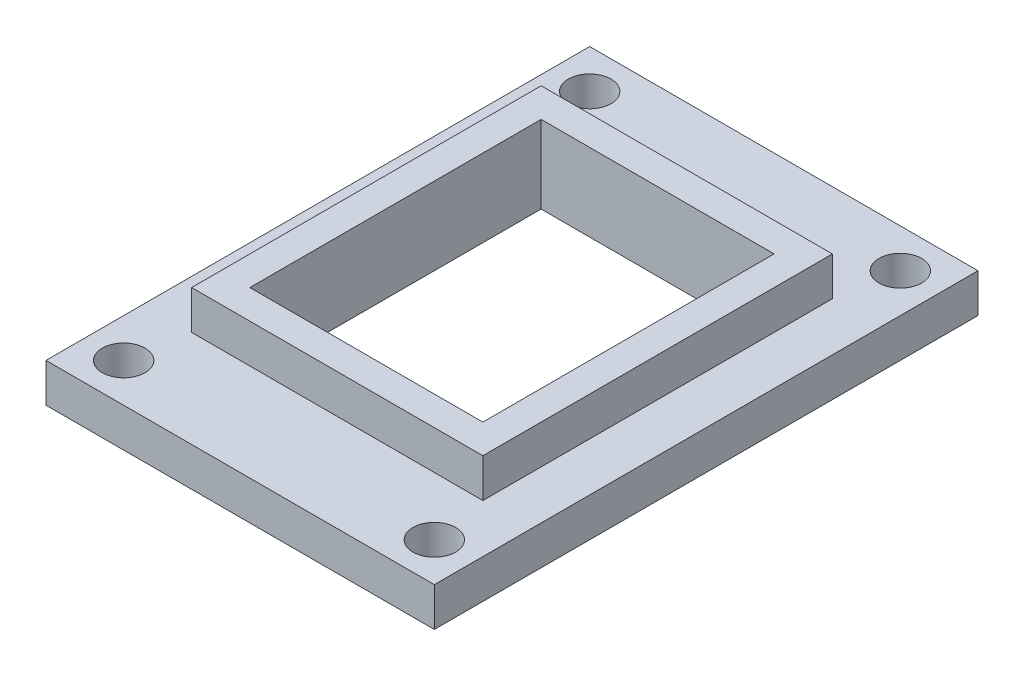
SolidWorks part; units mm, degrees
ref_plane "Front Plane" through (0, 0, 0) normal (0, 0, 1) x (1, 0, 0)
ref_plane "Top Plane" through (0, 0, 0) normal (0, 1, 0) x (1, 0, 0)
ref_plane "Right Plane" through (0, 0, 0) normal (1, 0, 0) x (0, 0, -1)
sketch "Sketch1" plane through (0, 0, 0) normal (0, 1, 0) x (1, 0, 0)
  line L0 (9.525, -11.43) -> (9.525, 11.43)
  line L1 (7.62, -9.525) -> (-7.62, -9.525)
  line L2 (7.62, -9.525) -> (7.62, 9.525)
  line L3 (7.62, 9.525) -> (-7.62, 9.525)
  line L4 (-7.62, -9.525) -> (-7.62, 9.525)
  line L5 (7.62, -9.525) -> (-7.62, 9.525) construction
  line L6 (7.62, 9.525) -> (-7.62, -9.525) construction
  line L7 (9.525, 11.43) -> (-9.525, 11.43)
  line L8 (-9.525, -11.43) -> (-9.525, 11.43)
  line L9 (9.525, -11.43) -> (-9.525, -11.43)
  point P0 (0, 0)
  dimension "D1" = 19.05
  dimension "D2" = 15.24
  dimension "D3" = 1.905
extrude "Boss-Extrude1" add sketch "Sketch1" along normal blind 5.08
sketch "Sketch3" plane through (0, 0, 0) normal (0, 1, 0) x (1, 0, 0)
  line L0 (-7.62, 0) -> (49992.38, 0) construction
  line L1 (-7.62, 9.525) -> (-7.62, -9.525) construction
  line L3 (0, 19.685) -> (0, -49980.315) construction
  line L4 (-9.525, -11.43) -> (9.525, -11.43)
  line L5 (9.525, -11.43) -> (9.525, 11.43)
  line L6 (9.525, 11.43) -> (-9.525, 11.43)
  line L7 (-9.525, 11.43) -> (-9.525, -11.43)
  line L8 (-9.525, -11.43) -> (9.525, -11.43)
  line L9 (9.525, -11.43) -> (9.525, 11.43)
  line L10 (9.525, 11.43) -> (-9.525, 11.43)
  line L11 (-9.525, 11.43) -> (-9.525, -11.43)
  line L12 (-7.62, -9.525) -> (7.62, -9.525) construction
  line L13 (-12.7, 17.78) -> (12.7, 17.78)
  line L14 (-12.7, 17.78) -> (-12.7, -17.78)
  line L15 (-12.7, -17.78) -> (12.7, -17.78)
  line L16 (12.7, 17.78) -> (12.7, -17.78)
  circle A0 centre (-10.16, 15.24) radius 1.397
  circle A1 centre (10.16, 15.24) radius 1.397
  circle A2 centre (-10.16, -15.24) radius 1.397
  circle A3 centre (10.16, -15.24) radius 1.397
  point P8 (-7.62, 0)
  point P11 (0, 11.43)
  point P14 (0, -9.525)
  point P23 (-12.7, 0)
  point P28 (0, 17.78)
  dimension "D2" = 2.794
  dimension "D3" = 30.48
  dimension "D5" = 2.54
  dimension "D4" = 20.32
  dimension "D6" = 2.54
  dimension "D1" = 0
extrude "Boss-Extrude2" add sketch "Sketch3" along normal blind 2.54
sketch "Sketch4" plane through (0, 5.08, 0) normal (0, 1, 0) x (1, 0, 0)
  line L1 (-10.16, 15.24) -> (10.16, 15.24) construction
  line L2 (-10.16, 15.24) -> (-10.16, -15.24) construction
  line L3 (-10.16, -15.24) -> (10.16, -15.24) construction
  line L4 (10.16, 15.24) -> (10.16, -15.24) construction
  circle A0 centre (-10.16, 15.24) radius 1.397 construction
  circle A1 centre (10.16, 15.24) radius 1.397 construction
  circle A2 centre (10.16, -15.24) radius 1.397 construction
  circle A3 centre (-10.16, -15.24) radius 1.397 construction
  circle A4 centre (-10.16, 15.24) radius 1.397
  circle A5 centre (10.16, 15.24) radius 1.397
  circle A6 centre (10.16, -15.24) radius 1.397
  circle A7 centre (-10.16, -15.24) radius 1.397
